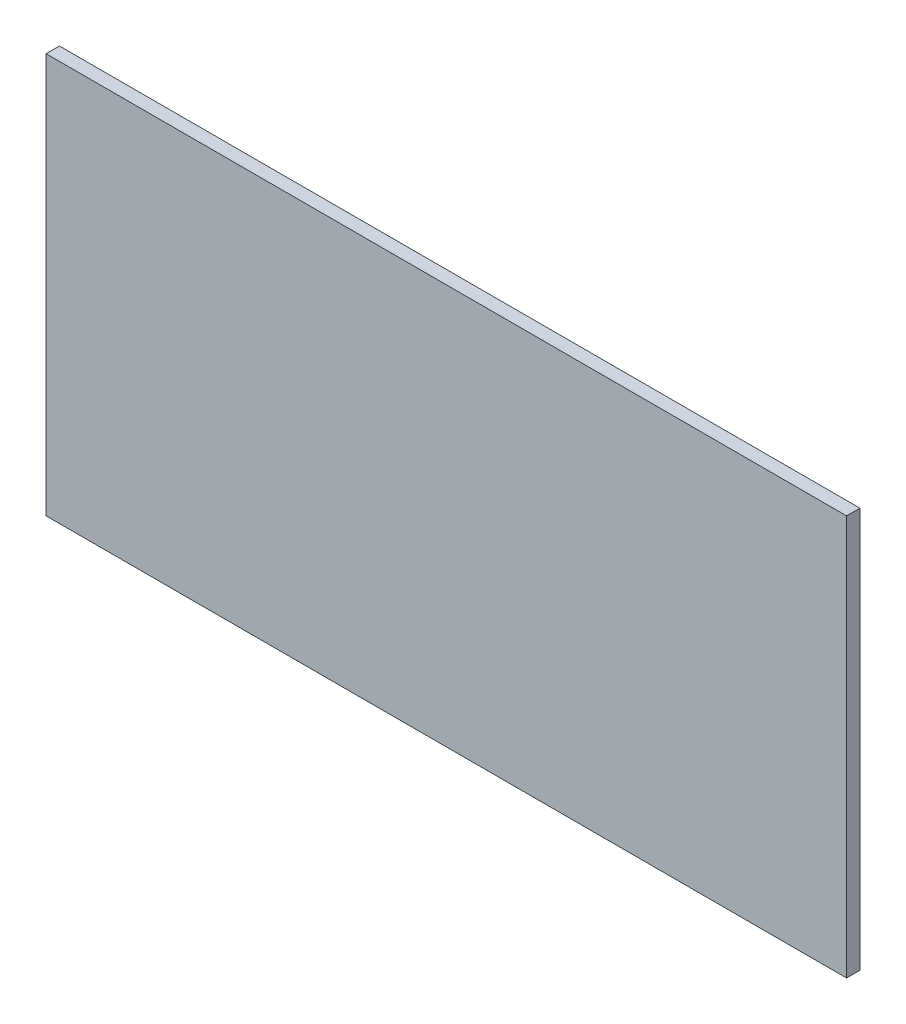
SolidWorks part; units mm, degrees
ref_plane "Front Plane" through (0, 0, 0) normal (0, 0, 1) x (1, 0, 0)
ref_plane "Top Plane" through (0, 0, 0) normal (0, 1, 0) x (1, 0, 0)
ref_plane "Right Plane" through (0, 0, 0) normal (1, 0, 0) x (0, 0, -1)
sketch "Sketch1" plane through (0, 0, -90) normal (0, 0, -1) x (-1, 0, 0)
  line L0 (60, 2) -> (60, 0) construction
  line L1 (-60, 0) -> (60, 0)
  line L2 (-60, 0) -> (-60, 60)
  line L3 (-60, 60) -> (60, 60)
  line L4 (60, 0) -> (60, 60)
  dimension "D1" = 60
extrude "Boss-Extrude1" add sketch "Sketch1" along normal blind 2 contours L2 L3 L4 L1
